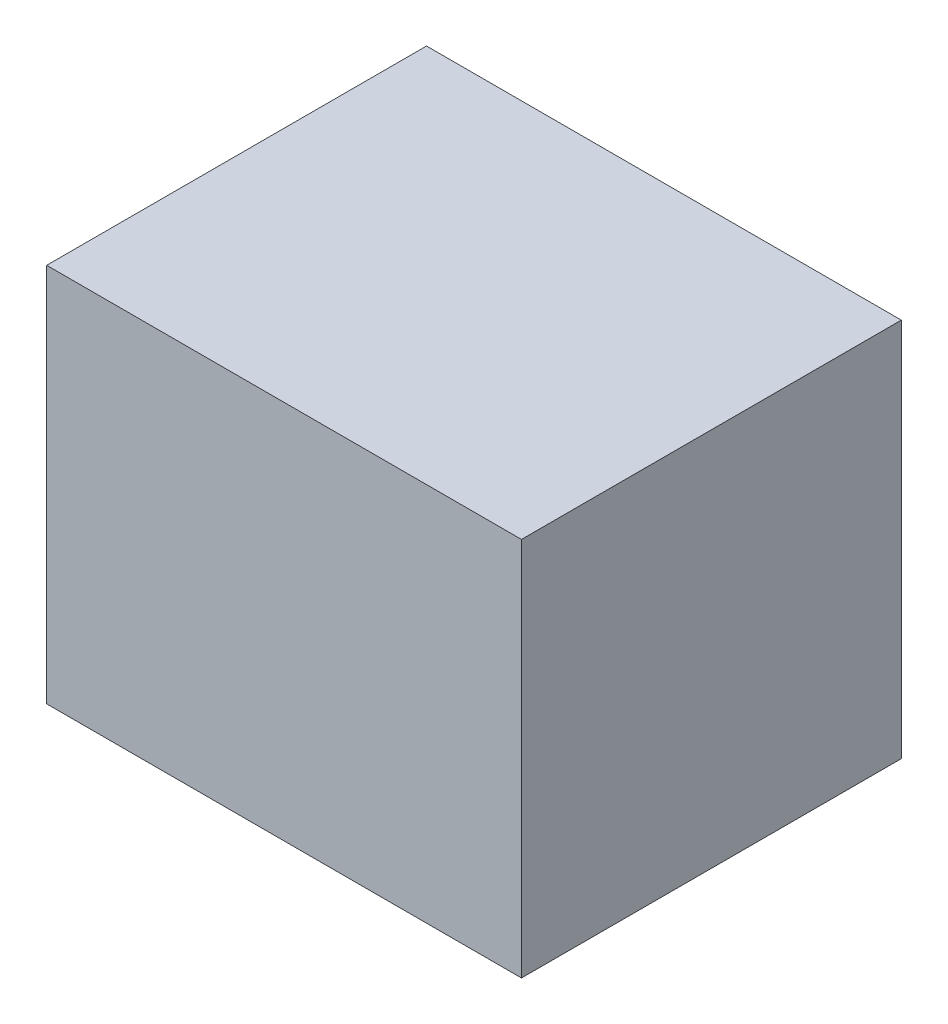
SolidWorks part; units mm, degrees
ref_plane "Front Plane" through (0, 0, 0) normal (0, 0, 1) x (1, 0, 0)
ref_plane "Top Plane" through (0, 0, 0) normal (0, 1, 0) x (1, 0, 0)
ref_plane "Right Plane" through (0, 0, 0) normal (1, 0, 0) x (0, 0, -1)
sketch "Sketch1" plane through (0, 0, 0) normal (0, 1, 0) x (1, 0, 0)
  line L1 (-12.5, 10) -> (12.5, 10)
  line L2 (-12.5, 10) -> (-12.5, -10)
  line L3 (-12.5, -10) -> (12.5, -10)
  line L4 (12.5, 10) -> (12.5, -10)
  line L5 (-12.5, 10) -> (12.5, -10) construction
  line L6 (-12.5, -10) -> (12.5, 10) construction
  point P0 (0, 0)
  dimension "D1" = 25
  dimension "D2" = 20
extrude "Boss-Extrude1" add sketch "Sketch1" along normal mid plane 20
